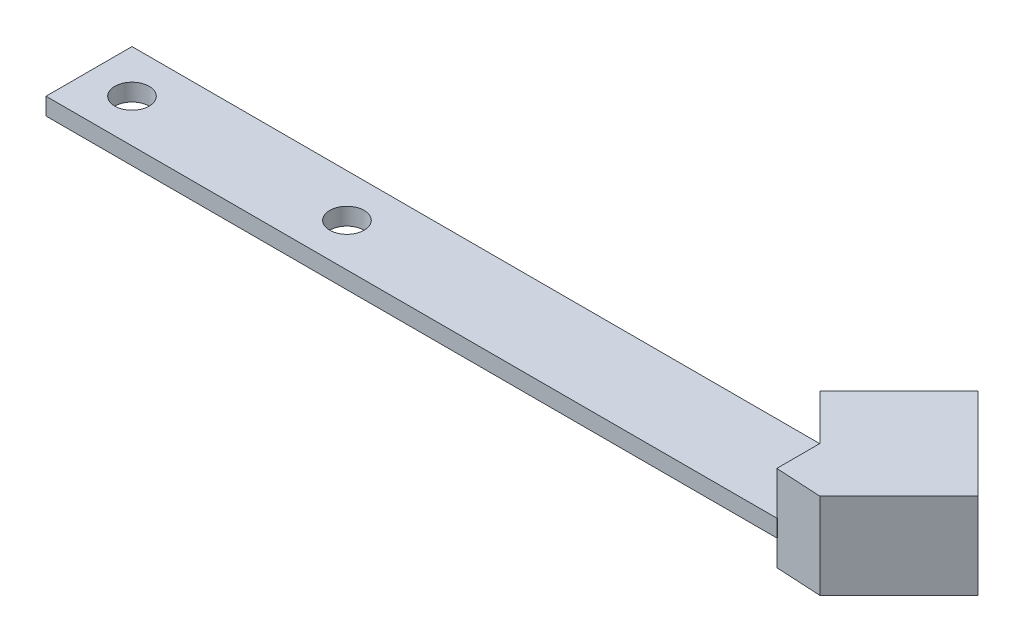
SolidWorks part; units mm, degrees
ref_plane "Front Plane" through (0, 0, 0) normal (0, 0, 1) x (1, 0, 0)
ref_plane "Top Plane" through (0, 0, 0) normal (0, 1, 0) x (1, 0, 0)
ref_plane "Right Plane" through (0, 0, 0) normal (1, 0, 0) x (0, 0, -1)
sketch "Sketch1" plane through (0, 0, 0) normal (0, 1, 0) x (1, 0, 0)
  line L1 (-24.2292, 7.0539) -> (60.7708, 7.0539)
  line L2 (-24.2292, 7.0539) -> (-24.2292, -2.9461)
  line L3 (-24.2292, -2.9461) -> (60.7708, -2.9461)
  line L4 (60.7708, 7.0539) -> (60.7708, -2.9461)
  circle A0 centre (-19.2292, 2.0539) radius 2
  circle A2 centre (5.7708, 2.0539) radius 2
  dimension "D3" = 5
  dimension "D5" = 25
  dimension "D1" = 10
  dimension "D2" = 85
extrude "Boss-Extrude1" add sketch "Sketch1" along normal blind 2
sketch "Sketch2" plane through (0, 2, 0) normal (0, 1, 0) x (1, 0, 0)
  line L0 (60.7708, 2.0539) -> (55.7708, 7.0539)
  line L1 (60.7708, -2.9461) -> (60.7708, 7.0539) construction
  line L2 (60.7708, 7.0539) -> (-24.2292, 7.0539) construction
  line L3 (55.7708, 7.0539) -> (60.7708, 7.0539)
  line L4 (60.7708, 7.0539) -> (60.7708, 2.0539)
  line L5 (60.7708, 2.0539) -> (60.7612, 2.0468)
  line M5 (60.7708, -2.9461) -> (60.7708, 7.0539)
  line M6 (60.7708, 7.0539) -> (-24.2292, 7.0539)
  dimension "D1" = 135
extrude "Cut-Extrude1" cut sketch "Sketch2" against normal blind 10 contours L0 M5 M6
sketch "Sketch3" plane through (31.4124, 0, -31.4124) normal (0.7071, 0, -0.7071) x (-0.7071, 0, -0.7071)
  line L1 (-33.9203, 6.9526) -> (-48.9203, 6.9526)
  line L2 (-33.9203, 6.9526) -> (-33.9203, -3.0474)
  line L3 (-33.9203, -3.0474) -> (-48.9203, -3.0474)
  line L4 (-48.9203, 6.9526) -> (-48.9203, -3.0474)
  dimension "D1" = 10
  dimension "D2" = 15
extrude "Boss-Extrude2" add sketch "Sketch3" along normal blind 13
sketch "Sketch4" plane through (0, 6.9526, 0) normal (0, 1, 0) x (1, 0, 0)
  line L0 (60.701, 2.1238) -> (60.701, -2.891)
  line L1 (55.3977, 7.4271) -> (66.0043, -3.1795) construction
  line L2 (60.701, -2.891) -> (66.0043, -3.1795)
  line L3 (66.0043, -3.1795) -> (60.701, 2.1238)
extrude "Boss-Extrude3" add sketch "Sketch4" against normal blind 10
